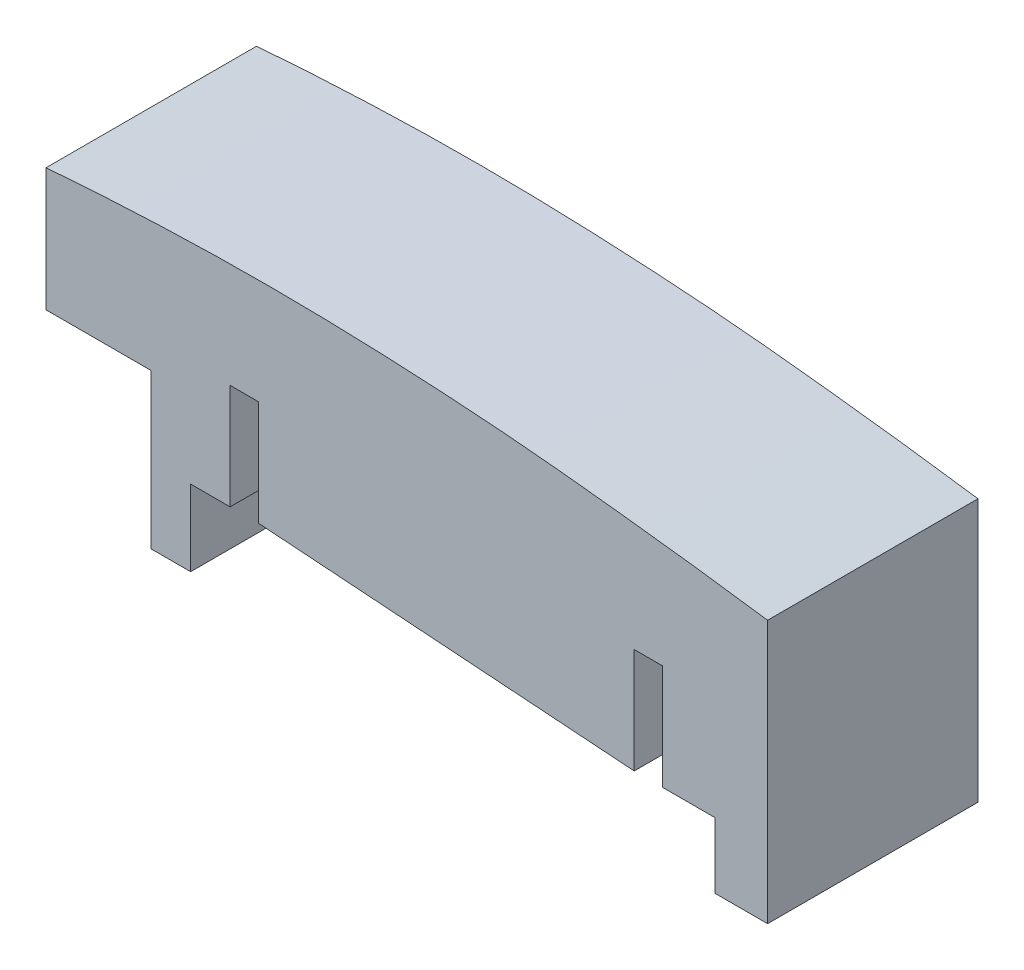
SolidWorks part; units mm, degrees
ref_plane "Front Plane" through (0, 0, 0) normal (0, 0, 1) x (1, 0, 0)
ref_plane "Top Plane" through (0, 0, 0) normal (0, 1, 0) x (1, 0, 0)
ref_plane "Right Plane" through (0, 0, 0) normal (1, 0, 0) x (0, 0, -1)
sketch "Sketch1" plane through (0, 0, 0) normal (0, 0, 1) x (1, 0, 0)
  line L0 (2220.6924, 2956.5195) -> (2207.9924, 2956.5195)
  line L1 (2220.6924, 2956.5195) -> (2220.6924, 2937.8714)
  line L2 (2207.9924, 2971.3735) -> (2207.9924, 2956.5195)
  line L3 (2230.2174, 2959.736) -> (2230.2174, 2947.036)
  line L4 (2233.621, 2959.736) -> (2233.621, 2947.036)
  line L5 (2282.4017, 2956.5112) -> (2282.4017, 2943.8112)
  line L6 (2295.1017, 2967.6255) -> (2295.1017, 2935.8971)
  line L7 (2278.9981, 2956.5112) -> (2278.9981, 2943.8112)
  line L8 (2282.4017, 2956.5112) -> (2278.9981, 2956.5112)
  line L9 (2288.7517, 2943.8112) -> (2282.4017, 2943.8112)
  line L10 (2230.2174, 2959.736) -> (2233.621, 2959.736)
  line L11 (2225.4549, 2947.036) -> (2230.2174, 2947.036)
  line L12 (2233.621, 2947.036) -> (2278.9981, 2943.8112)
  line L13 (2225.4549, 2947.036) -> (2225.4549, 2937.8714)
  line L14 (2288.7517, 2943.8112) -> (2288.7517, 2935.8971)
  line L15 (2225.4549, 2937.8714) -> (2220.6924, 2937.8714)
  line L16 (2288.7517, 2935.8971) -> (2295.1017, 2935.8971)
  spline S0 degree 3 poles (2295.1017, 2967.6255) (2290.0644, 2968.3461) (2285.0123, 2969.0082) (2275.6617, 2970.0959) (2271.4689, 2970.562) (2263.7126, 2971.2841) (2260.2218, 2971.5442) (2253.376, 2971.9627) (2249.9444, 2972.1308) (2239.6306, 2972.4949) (2232.6844, 2972.5394) (2220.0261, 2972.178) (2214.3536, 2971.8758) (2208.6346, 2971.4247) (2208.4206, 2971.4078) (2208.2065, 2971.3907) (2207.9924, 2971.3735) knots 8.102631 8.102631 8.102631 8.102631 8.693015 8.693015 9.188395 9.188395 9.581929 9.581929 9.975462 9.975462 10.762529 10.762529 11.414127 11.414127 11.414127 11.438511 11.438511 11.438511 11.438511
extrude "Boss-Extrude1" add sketch "Sketch1" along normal blind 25.4
